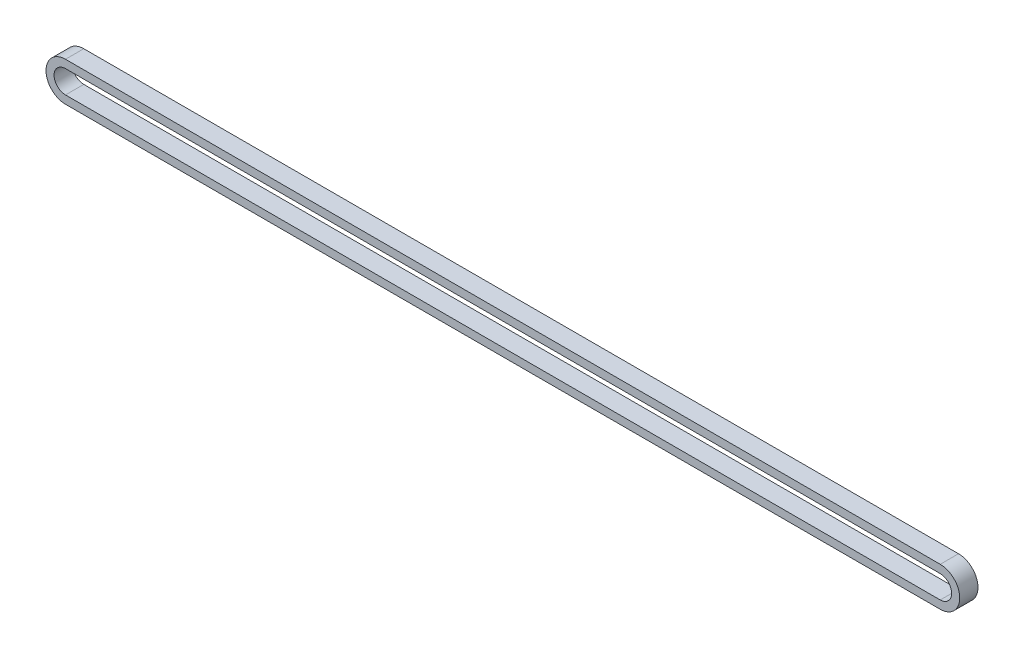
SolidWorks part; units mm, degrees
ref_plane "Front Plane" through (0, 0, 0) normal (0, 0, 1) x (1, 0, 0)
ref_plane "Top Plane" through (0, 0, 0) normal (0, 1, 0) x (1, 0, 0)
ref_plane "Right Plane" through (0, 0, 0) normal (1, 0, 0) x (0, 0, -1)
sketch "Sketch1" plane through (0, 0, 0) normal (0, 0, 1) x (1, 0, 0)
  line L9 (0, 3.2) -> (143.6, 3.2)
  line L10 (0, 1.872) -> (143.6, 1.872)
  line L11 (0, -3.2) -> (143.6, -3.2)
  line L12 (0, -1.872) -> (143.6, -1.872)
  circle A16 centre (0, 0) radius 3.2 construction
  arc A17 (0, 3.2) -> (0, -3.2) centre (0, 0) ccw
  circle A18 centre (0, 0) radius 1.872 construction
  arc A19 (0, 1.872) -> (0, -1.872) centre (0, 0) ccw
  circle A20 centre (143.6, 0) radius 1.872 construction
  circle A21 centre (143.6, 0) radius 3.2 construction
  arc A22 (143.6, -1.872) -> (143.6, 1.872) centre (143.6, 0) ccw
  arc A23 (143.6, -3.2) -> (143.6, 3.2) centre (143.6, 0) ccw
extrude "Boss-Extrude1" add sketch "Sketch1" along normal blind 3
